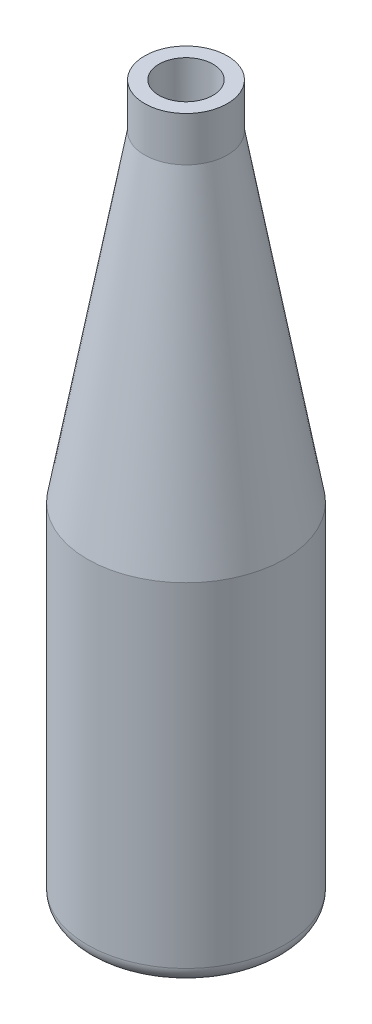
SolidWorks part; units mm, degrees
ref_plane "Piano frontale" through (0, 0, 0) normal (0, 0, 1) x (1, 0, 0)
ref_plane "Piano superiore" through (0, 0, 0) normal (0, 1, 0) x (1, 0, 0)
ref_plane "Piano destro" through (0, 0, 0) normal (1, 0, 0) x (0, 0, -1)
sketch "Schizzo1" plane through (0, 0, 0) normal (0, 0, 1) x (1, 0, 0)
  line L0 (0, 0) -> (-26, 0)
  line L1 (-31, 5) -> (-31, 110)
  line L2 (-31, 110) -> (-13, 211)
  line L3 (-13, 211) -> (-13, 225)
  line L4 (-13, 225) -> (-8.5, 225)
  line L5 (0, 225) -> (0, 0) construction
  line L6 (-8.5, 210.6021) -> (-8.5, 220.5)
  line L9 (-4.5, 4.5) -> (-26, 4.5)
  line L10 (-26.5, 5) -> (-26.5, 109.6021)
  line L11 (-26.5, 109.6021) -> (-8.5, 210.6021)
  line L12 (-8.5, 220.5) -> (-4.5, 220.5) construction
  line L13 (-4.5, 220.5) -> (-4.5, 4.5) construction
  line L14 (-4.5, 4.5) -> (0, 4.5)
  line L15 (-8.5, 220.5) -> (-8.5, 225)
  line L16 (-13, 225) -> (0, 225) construction
  line L17 (0, 4.5) -> (0, 0)
  arc A0 (-26, 0) -> (-31, 5) centre (-26, 5) cw
  arc A1 (-26, 4.5) -> (-26.5, 5) centre (-26, 5) cw
  point P9 (-31, 0)
  dimension "D6" = 5
  dimension "D1" = 31
  dimension "D2" = 110
  dimension "D3" = 13
  dimension "D4" = 14
  dimension "D5" = 225
revolve "Rivoluzione1" add sketch "Schizzo1" angle 360 about L5
